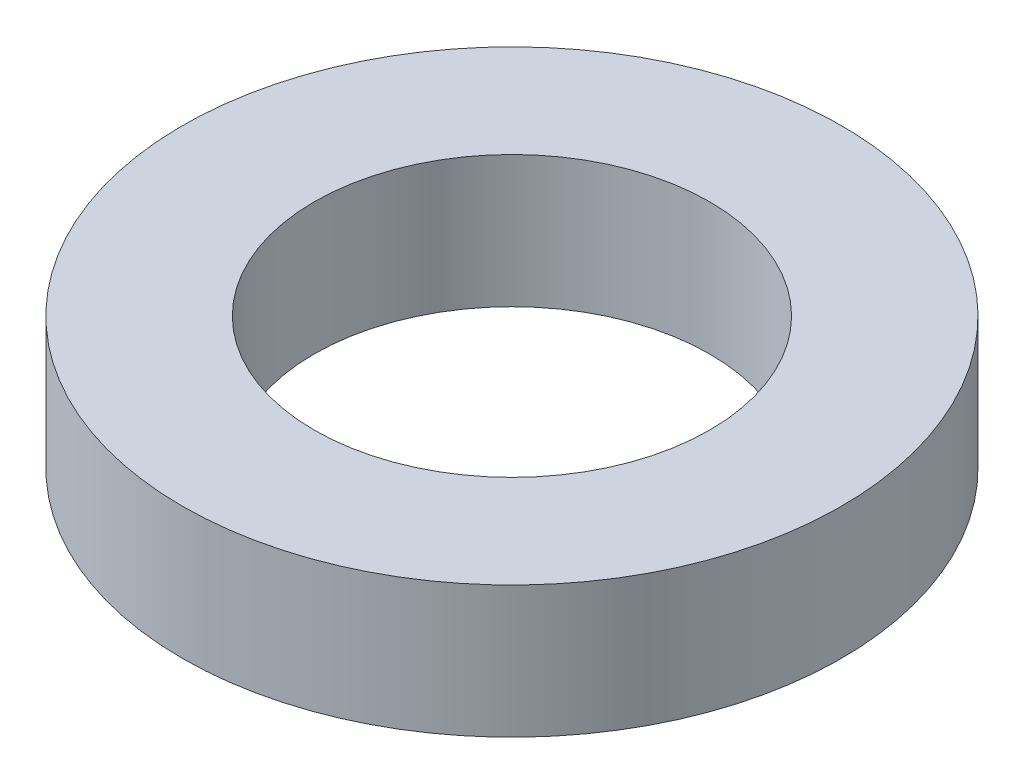
SolidWorks part; units mm, degrees
ref_plane "前视基准面" through (0, 0, 0) normal (0, 0, 1) x (1, 0, 0)
ref_plane "上视基准面" through (0, 0, 0) normal (0, 1, 0) x (1, 0, 0)
ref_plane "右视基准面" through (0, 0, 0) normal (1, 0, 0) x (0, 0, -1)
sketch "草图1" plane through (0, 0, 0) normal (0, 1, 0) x (1, 0, 0)
  circle A1 centre (0, 0) radius 25
extrude "凸台-拉伸1" add sketch "草图1" along normal blind 10
sketch "草图2" plane through (0, 0, 0) normal (0, 1, 0) x (1, 0, 0)
  circle A0 centre (0, 0) radius 15
extrude "切除-拉伸1" cut sketch "草图2" along normal through all
